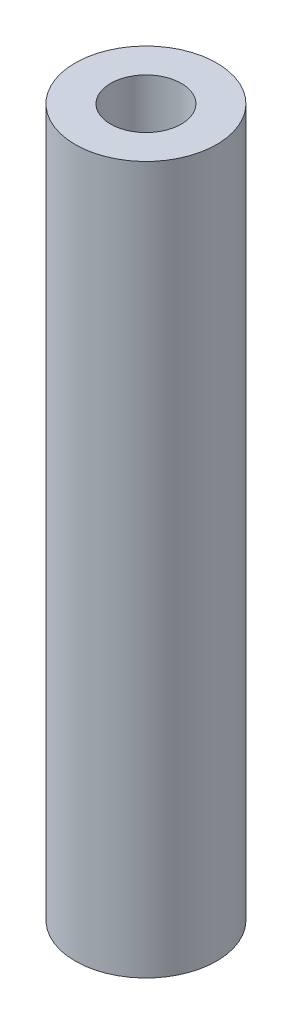
SolidWorks part; units mm, degrees
ref_plane "정면" through (0, 0, 0) normal (0, 0, 1) x (1, 0, 0)
ref_plane "윗면" through (0, 0, 0) normal (0, 1, 0) x (1, 0, 0)
ref_plane "우측면" through (0, 0, 0) normal (1, 0, 0) x (0, 0, -1)
sketch "스케치1" plane through (0, 0, 0) normal (0, 1, 0) x (1, 0, 0)
  circle A0 centre (0, 0) radius 3
  dimension "D1" = 6
extrude "보스-돌출1" add sketch "스케치1" along normal blind 30
sketch "스케치2" plane through (0, 30, 0) normal (0, 1, 0) x (1, 0, 0)
  circle A0 centre (0, 0) radius 1.5
  dimension "D1" = 3
extrude "컷-돌출1" cut sketch "스케치2" against normal blind 6
